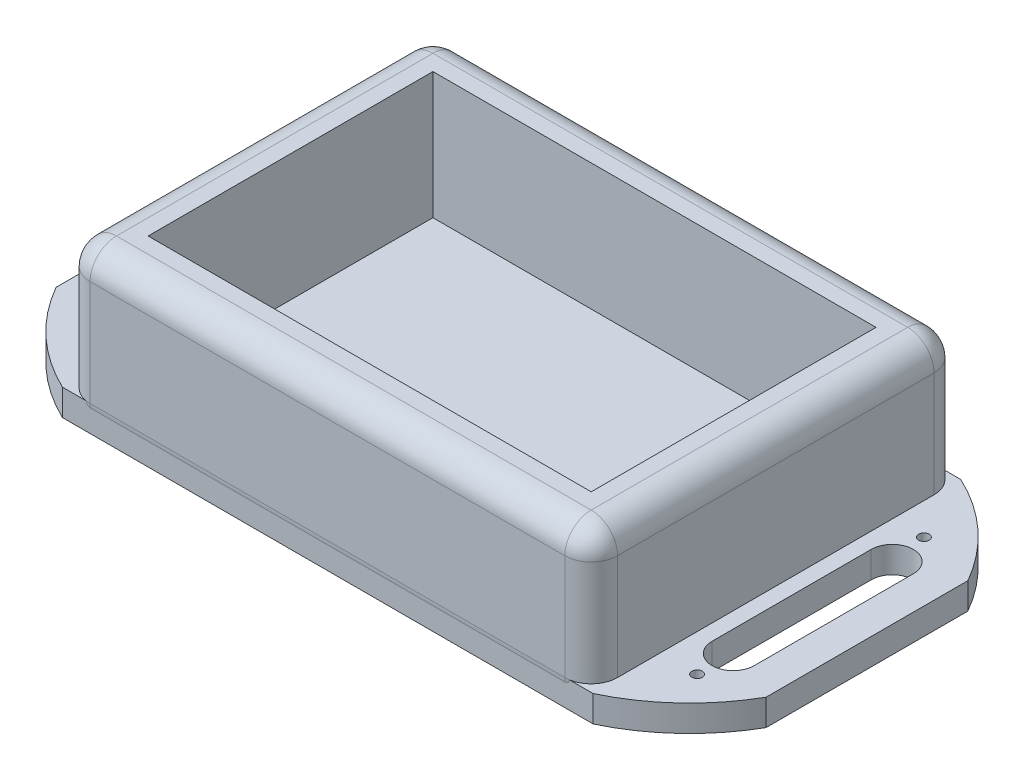
SolidWorks part; units mm, degrees
ref_plane "Front Plane" through (0, 0, 0) normal (0, 0, 1) x (1, 0, 0)
ref_plane "Top Plane" through (0, 0, 0) normal (0, 1, 0) x (1, 0, 0)
ref_plane "Right Plane" through (0, 0, 0) normal (1, 0, 0) x (0, 0, -1)
other "Center of Mass"
sketch "Sketch1" plane through (0, 0, 0) normal (0, 1, 0) x (1, 0, 0)
  line L0 (23.3839, 15.8839) -> (-23.3839, -15.8839) construction
  line L1 (-23.3839, 16.6161) -> (21.6161, 16.6161)
  line L2 (-25.8839, 14.1161) -> (-25.8839, -15.8839)
  line L3 (-23.3839, -18.3839) -> (21.6161, -18.3839)
  line L4 (24.1161, 14.1161) -> (24.1161, -15.8839)
  arc A0 (-23.3839, 16.6161) -> (-25.8839, 14.1161) centre (-23.3839, 14.1161) ccw
  arc A1 (21.6161, 16.6161) -> (24.1161, 14.1161) centre (21.6161, 14.1161) cw
  arc A2 (21.6161, -18.3839) -> (24.1161, -15.8839) centre (21.6161, -15.8839) ccw
  arc A3 (-25.8839, -15.8839) -> (-23.3839, -18.3839) centre (-23.3839, -15.8839) ccw
  point P6 (-25.8839, 16.6161)
  point P9 (24.1161, 16.6161)
  point P14 (-25.8839, -18.3839)
  point P16 (0, 0)
  dimension "D3" = 2.5
  dimension "D4" = 2.5
  dimension "D5" = 2.5
  dimension "D6" = 2.5
  dimension "D1" = 50
  dimension "D2" = 35
extrude "Boss-Extrude2" add sketch "Sketch1" along normal blind 15
fillet "Fillet2" radius 2.5 16 edges at (-25.8839, 0, 0.8839) (-25.1517, 0, 17.6517) (-0.8839, 0, 18.3839) (23.3839, 0, 17.6517) (24.1161, 0, 0.8839) (23.3839, 0, -15.8839) (-0.8839, 0, -16.6161) (-25.1517, 0, -15.8839) (-0.8839, 15, -16.6161) (23.3839, 15, -15.8839) (24.1161, 15, 0.8839) (23.3839, 15, 17.6517) (-0.8839, 15, 18.3839) (-25.1517, 15, 17.6517) (-25.8839, 15, 0.8839) (-25.1517, 15, -15.8839)
sketch "Sketch3" plane through (0, 0, 0) normal (0, 1, 0) x (1, 0, 0)
  line L0 (21.6161, 14.1161) -> (-23.3839, 14.1161) construction
  line L1 (-0.8839, 14.1161) -> (-0.8839, -15.8839)
  line L2 (-25.8839, 16.6469) -> (24.1161, 16.6469)
  line L3 (-34.5339, 8.6743) -> (-34.5339, -10.4535)
  line L4 (-26.039, -18.3531) -> (24.2713, -18.3531)
  line L6 (29.6161, 6.6585) -> (29.6161, -8.4263)
  line L7 (25.6161, 6.6585) -> (25.6161, -8.4263)
  line L8 (32.7661, 8.6743) -> (32.7661, -10.4535)
  line L9 (-23.3839, -15.8839) -> (21.6161, -15.8839) construction
  line L10 (32.7661, 8.6743) -> (32.7661, -10.4535)
  line L14 (-31.3839, 6.6585) -> (-31.3839, -8.4263)
  line L16 (-27.3839, 6.6585) -> (-27.3839, -8.4263)
  circle A0 centre (-28.8839, 10.1585) radius 0.5
  circle A1 centre (-29.3839, -11.8415) radius 0.5
  circle A2 centre (27.6161, -11.8415) radius 0.5
  circle A3 centre (27.1161, 10.1585) radius 0.5
  arc A4 (-27.3839, 6.6585) -> (-31.3839, 6.6585) centre (-29.3839, 6.6585) ccw
  arc A5 (-27.3839, -8.4263) -> (-31.3839, -8.4263) centre (-29.3839, -8.4263) cw
  arc A6 (25.6161, -8.4263) -> (29.6161, -8.4263) centre (27.6161, -8.4263) ccw
  arc A7 (25.6161, 6.6585) -> (29.6161, 6.6585) centre (27.6161, 6.6585) cw
  arc A8 (32.7661, -10.4535) -> (24.2713, -18.3531) centre (15.952, -0.8896) cw
  arc A9 (-34.5339, -10.4535) -> (-26.039, -18.3531) centre (-17.7198, -0.8896) ccw
  arc A10 (-25.8839, 16.6469) -> (-34.5339, 8.6743) centre (-17.7198, -0.8896) ccw
  arc A11 (24.1161, 16.6469) -> (32.7661, 8.6743) centre (15.952, -0.8896) cw
  dimension "D5" = 35
  dimension "D1" = 67.3
  dimension "D2" = 22
  dimension "D3" = 56
  dimension "D4" = 50
extrude "Boss-Extrude4" add sketch "Sketch3" along normal blind 2.5
other "Center of Mass Reference Point2"
sketch "Sketch4" plane through (0, 15, 0) normal (0, 1, 0) x (1, 0, 0)
  line L9 (-21.8841, 12.6165) -> (20.1187, 12.6165)
  line L10 (-21.8841, 12.6165) -> (-21.8841, -14.3846)
  line L11 (-21.8841, -14.3846) -> (20.1187, -14.3846)
  line L12 (20.1187, 12.6165) -> (20.1187, -14.3846)
  line L13 (-21.8841, 12.6165) -> (20.1187, -14.3846) construction
  line L14 (-21.8841, -14.3846) -> (20.1187, 12.6165) construction
  point P0 (-0.8827, -0.8841)
extrude "Cut-Extrude1" cut sketch "Sketch4" against normal blind 12 contours L12 L9 L10 L11
